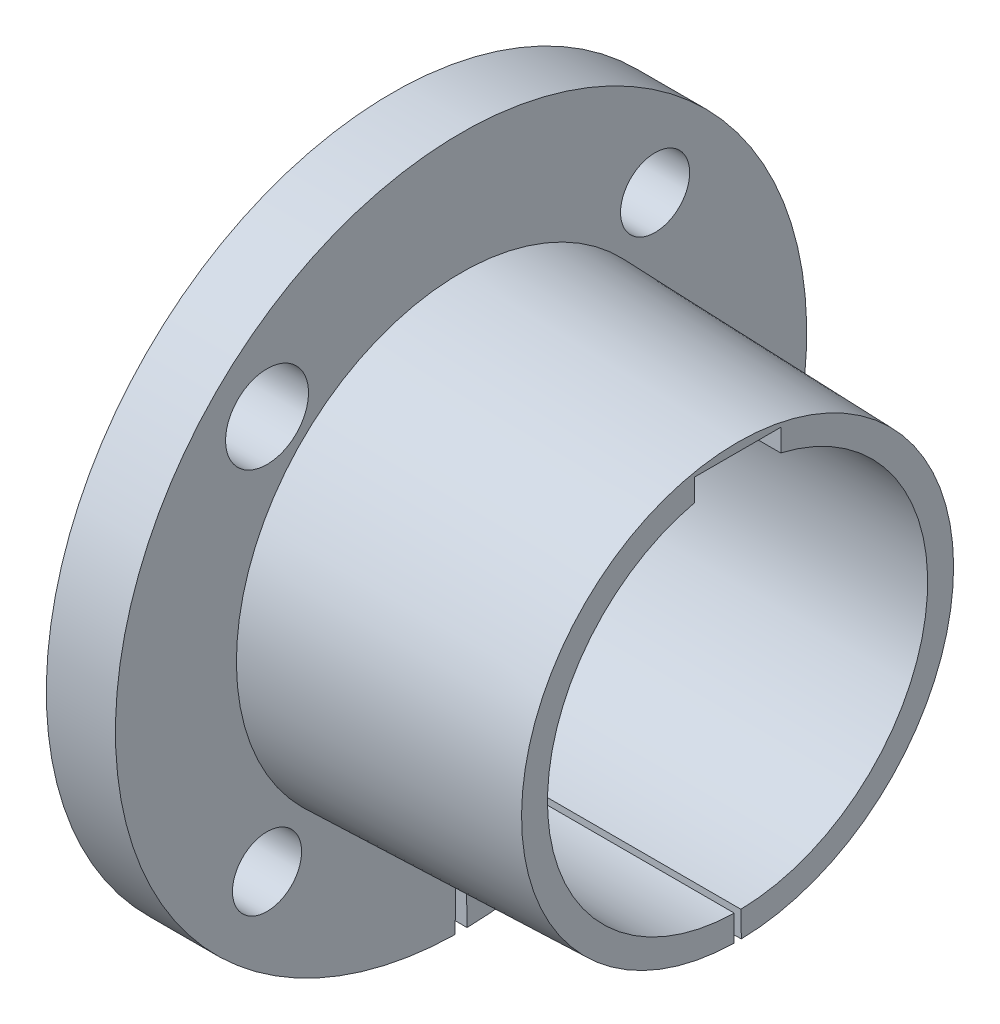
SolidWorks part; units mm, degrees
ref_plane "Front Plane" through (0, 0, 0) normal (0, 0, 1) x (1, 0, 0)
ref_plane "Top Plane" through (0, 0, 0) normal (0, 1, 0) x (1, 0, 0)
ref_plane "Right Plane" through (0, 0, 0) normal (1, 0, 0) x (0, 0, -1)
ref_plane "Plane1" through (0, 0, 0) normal (0, -0.0175, -0.9998) x (1, 0, 0)
sketch "Sketch1" plane through (0, 0, 0) normal (0, -0.0175, -0.9998) x (1, 0, 0)
  line L0 (-6.35, 31.75) -> (-6.35, 17.4625)
  line L1 (-6.35, 17.4625) -> (25.4, 17.4625)
  line L2 (25.4, 17.4625) -> (25.4, 31.75)
  line L3 (25.4, 31.75) -> (-6.35, 31.75)
  line L4 (-6.35, 0) -> (25.4, 0) construction
revolve "Revolve1" add sketch "Sketch1" angle 358 about L4
sketch "Sketch2" plane through (-6.35, 0, 0) normal (-1, 0, 0) x (0, 0, 1)
  line L0 (3.9688, 17.0055) -> (3.9688, 19.05)
  line L1 (3.9688, 19.05) -> (-3.9688, 19.05)
  line L2 (-3.9688, 19.05) -> (-3.9687, 17.0055)
  arc A0 (-3.9687, 17.0055) -> (3.9688, 17.0055) centre (0, 0) cw
extrude "Cut-Extrude1" cut sketch "Sketch2" against normal through all
sketch "Sketch3" plane through (25.4, 0, 0) normal (1, 0, 0) x (0, 0, -1)
  line L0 (0.3602, -20.6344) -> (0.5541, -31.7452)
  line L1 (-0.5541, -31.7452) -> (-0.3602, -20.6344)
  arc A0 (-0.3602, -20.6344) -> (0.3602, -20.6344) centre (0, 0) cw
  arc A1 (0.5541, -31.7452) -> (-0.5541, -31.7452) centre (0, 0) ccw
extrude "Cut-Extrude2" cut sketch "Sketch3" against normal blind 25.4
draft "Draft1" type of draft neutral plane draft angle 1.79 faces to draft 1 face at (12.7, 0.0016, 0) neutral plane through (0, 0, 0) neutral plane normal (1, 0, 0) parameters "D1"=1.79
hole_wizard "M7 Clearance Hole1" positions "Sketch5" profile "Sketch4" hole size "M7" standard "ANSI Metric"
sketch "Sketch5" plane through (-6.35, 0, 0) normal (-1, 0, 0) x (0, 0, 1)
  point P0 (-17.8232, -18.0967)
  point P1 (17.8232, 18.0967)
sketch "Sketch4" plane through (-6.35, -18.0967, -17.8232) normal (0, 1, 0) x (0, 0, 1)
  line L0 (0, 0) -> (0, 31.75)
  line L1 (0, 31.75) -> (3.81, 31.75)
  line L2 (3.81, 31.75) -> (3.81, 0)
  line L5 (3.81, 0) -> (0, 0)
  line L11 (0, -6.35) -> (0, 107.95) construction
  dimension "Thru Hole Dia." = 7.62
  dimension "Thru Hole Depth" = 31.75
hole_wizard "Hole1" positions "Sketch7" profile "Sketch6" legacy
sketch "Sketch7" plane through (-6.35, 0, 0) normal (-1, 0, 0) x (0, 0, 1)
  point P0 (-17.8232, 18.0967)
  point P1 (17.8232, -18.0967)
sketch "Sketch6" plane through (-6.35, 18.0967, -17.8232) normal (0, 1, 0) x (0, 0, 1)
  line L0 (0, 0) -> (0, 31.75)
  line L1 (0, 31.75) -> (3.175, 31.75)
  line L2 (3.175, 31.75) -> (3.175, 0)
  line L3 (3.175, 0) -> (0, 0)
  line L4 (0, 110) -> (0, -10) construction
  dimension "Diameter" = 6.35
  dimension "Depth" = 31.75
